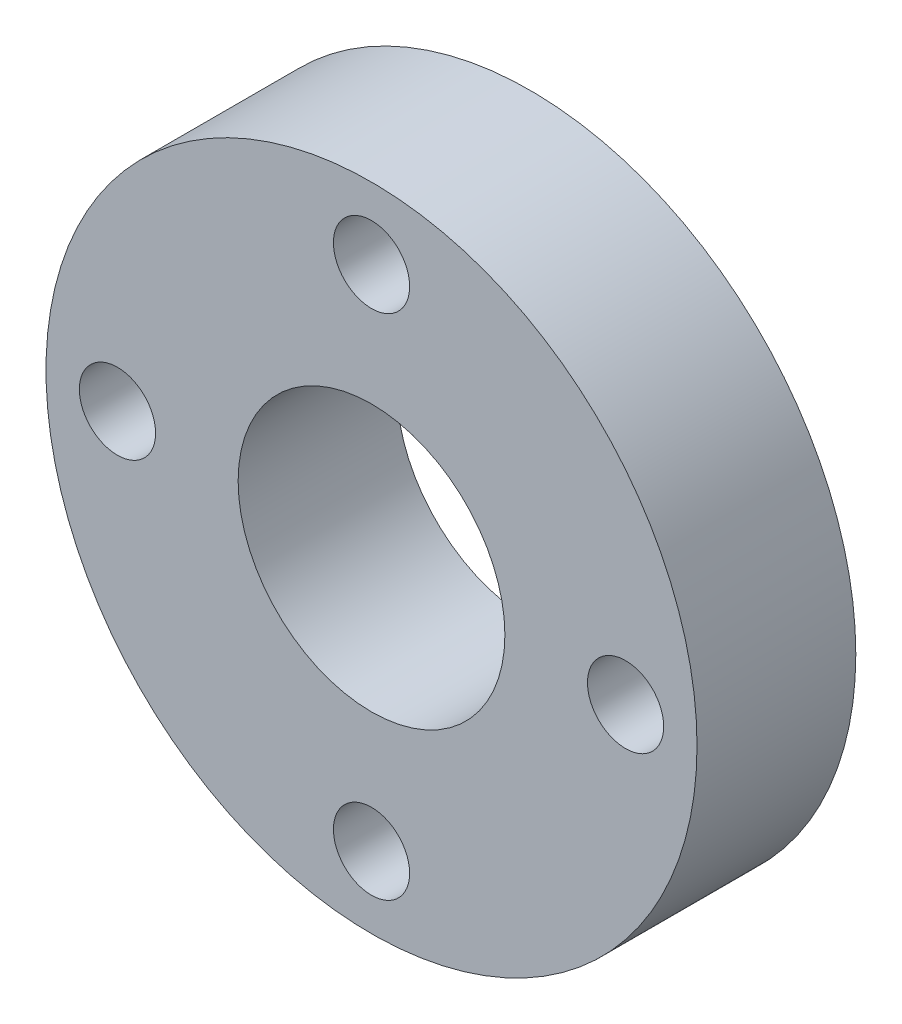
SolidWorks part; units mm, degrees
ref_plane "Front Plane" through (0, 0, 0) normal (0, 0, 1) x (1, 0, 0)
ref_plane "Top Plane" through (0, 0, 0) normal (0, 1, 0) x (1, 0, 0)
ref_plane "Right Plane" through (0, 0, 0) normal (1, 0, 0) x (0, 0, -1)
sketch "Sketch1" plane through (0, 0, 0) normal (0, 0, 1) x (1, 0, 0)
  circle A0 centre (0, 0) radius 10.25
  circle A1 centre (0, 0) radius 4.2
  circle A2 centre (0, 0) radius 8
  circle A3 centre (0, 8) radius 1.2
  circle A4 centre (8, 0) radius 1.2
  circle A5 centre (0, -8) radius 1.2
  circle A6 centre (-8, 0) radius 1.2
  point P17 (0, 0)
  dimension "D1" = 4
extrude "Boss-Extrude1" add sketch "Sketch1" along normal blind 5 contours A0 A6 A2 A3 A4 A5 | A6 A2 A5 A4 A3 A1
